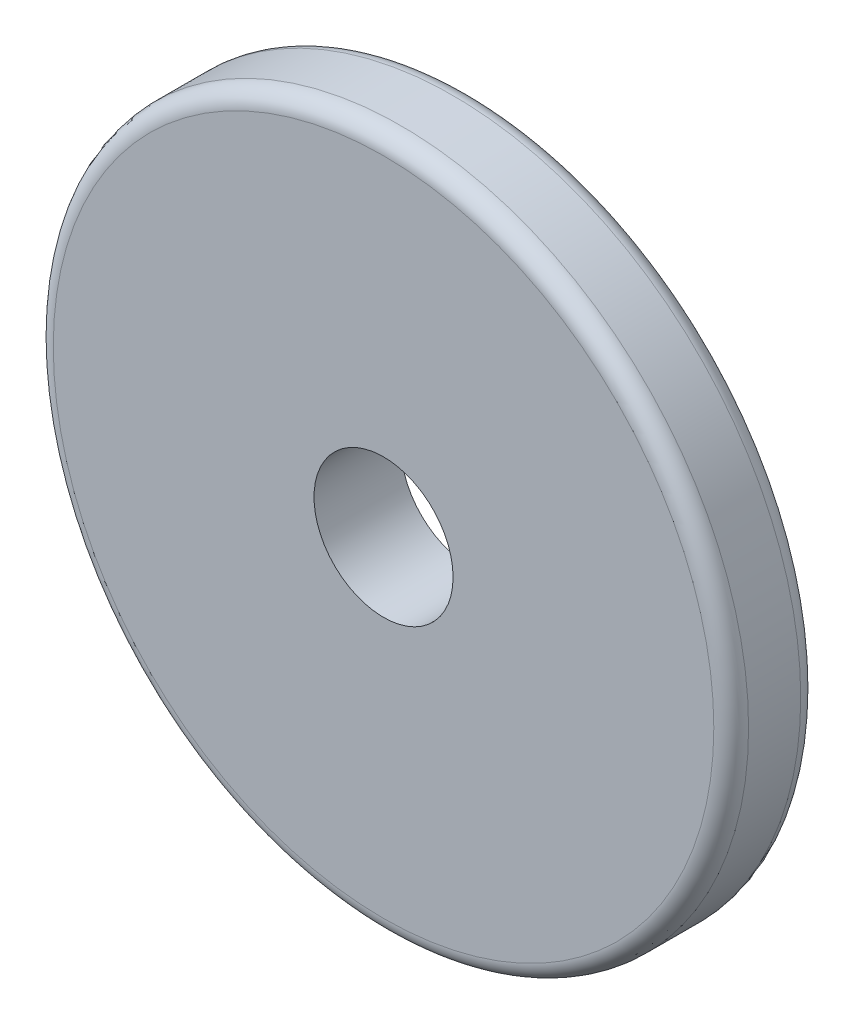
SolidWorks part; units mm, degrees
ref_plane "Front Plane" through (0, 0, 0) normal (0, 0, 1) x (1, 0, 0)
ref_plane "Top Plane" through (0, 0, 0) normal (0, 1, 0) x (1, 0, 0)
ref_plane "Right Plane" through (0, 0, 0) normal (1, 0, 0) x (0, 0, -1)
sketch "Sketch1" plane through (0, 0, 0) normal (0, 0, 1) x (1, 0, 0)
  circle A0 centre (0, 0) radius 20
  circle A1 centre (0, 0) radius 4
  dimension "D1" = 40
  dimension "D2" = 8
extrude "Boss-Extrude1" add sketch "Sketch1" along normal blind 5
fillet "Fillet1" radius 1 2 edges at (20, 0, 5) (20, 0, 0)
